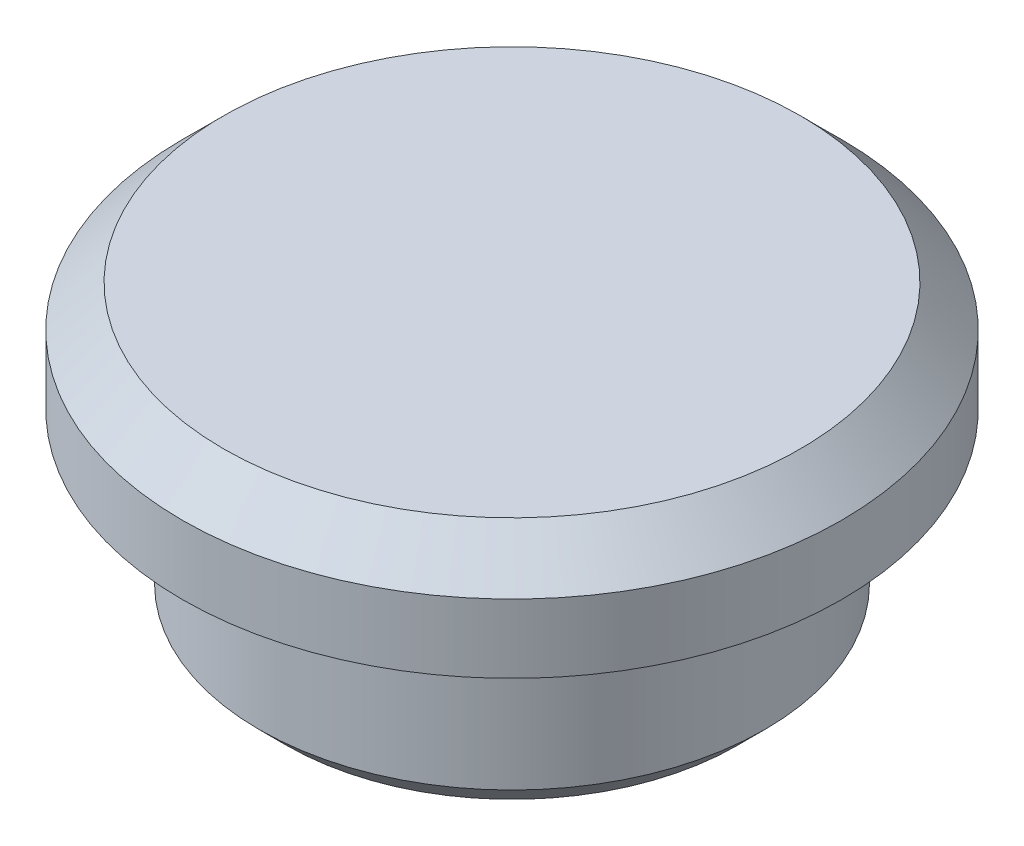
SolidWorks part; units mm, degrees
ref_plane "Front Plane" through (0, 0, 0) normal (0, 0, 1) x (1, 0, 0)
ref_plane "Top Plane" through (0, 0, 0) normal (0, 1, 0) x (1, 0, 0)
ref_plane "Right Plane" through (0, 0, 0) normal (1, 0, 0) x (0, 0, -1)
sketch "Sketch1" plane through (0, 0, 0) normal (0, 1, 0) x (1, 0, 0)
  circle A0 centre (0, 0) radius 4.6736
  dimension "D1" = 9.3472
extrude "Boss-Extrude1" add sketch "Sketch1" along normal blind 3.302
sketch "Sketch2" plane through (0, 3.302, 0) normal (0, 1, 0) x (1, 0, 0)
  circle A0 centre (0, 0) radius 6.096
  dimension "D1" = 12.192
extrude "Boss-Extrude2" add sketch "Sketch2" along normal blind 2.032
chamfer "Chamfer1" distance 0.762 angle 45 1 edges at (0, 5.334, 6.096)
chamfer "Chamfer2" distance 0.508 angle 45 1 edges at (0, 0, 4.6736)
